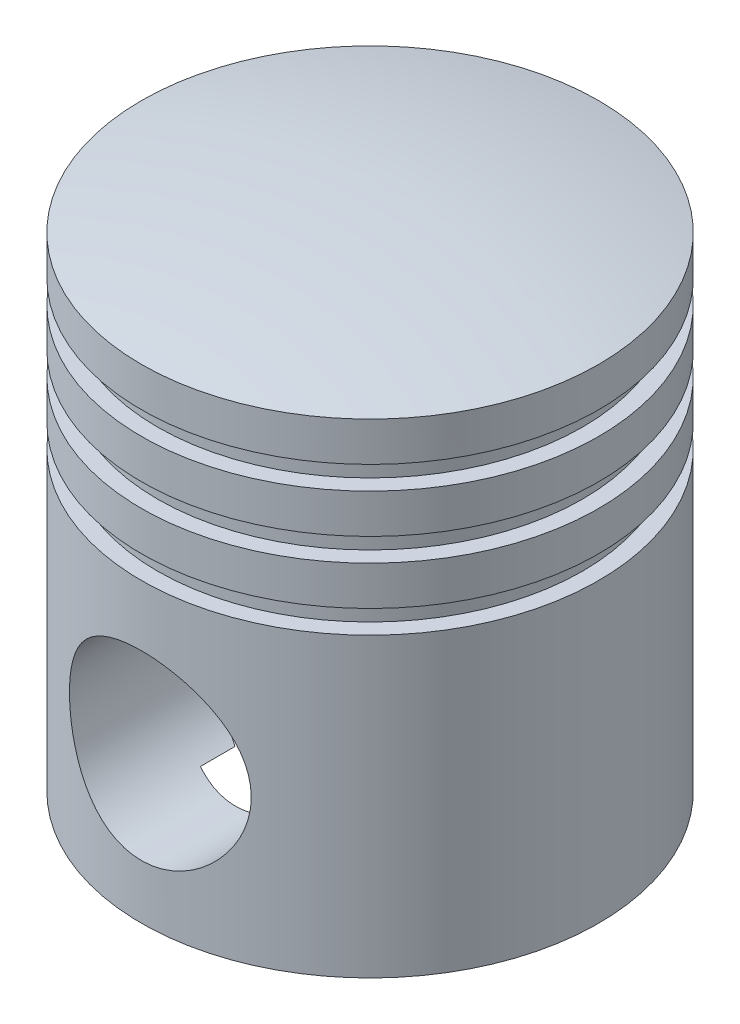
SolidWorks part; units mm, degrees
ref_plane "Front Plane" through (0, 0, 0) normal (0, 0, 1) x (1, 0, 0)
ref_plane "Top Plane" through (0, 0, 0) normal (0, 1, 0) x (1, 0, 0)
ref_plane "Right Plane" through (0, 0, 0) normal (1, 0, 0) x (0, 0, -1)
sketch "Sketch5" plane through (0, 0, 0) normal (0, 0, 1) x (1, 0, 0)
  line L0 (0, 0) -> (0, 123.193) construction
  line L1 (25, 0) -> (42.5, 0)
  line L2 (42.5, 0) -> (42.5, 55.2)
  line L3 (42.5, 55.2) -> (39.5, 55.2)
  line L4 (39.5, 55.2) -> (39.5, 59.5)
  line L5 (39.5, 59.5) -> (42.5, 59.5)
  line L6 (42.5, 59.5) -> (42.5, 66.8)
  line L7 (42.5, 66.8) -> (39.5, 66.8)
  line L8 (39.5, 66.8) -> (39.5, 71.1)
  line L9 (39.5, 71.1) -> (42.5, 71.1)
  line L10 (42.5, 71.1) -> (42.5, 78.4)
  line L11 (42.5, 78.4) -> (39.5, 78.4)
  line L12 (39.5, 78.4) -> (39.5, 82.7)
  line L13 (39.5, 82.7) -> (42.5, 82.7)
  line L14 (42.5, 82.7) -> (42.5, 90)
  line L16 (0, 90) -> (0, 85)
  line L17 (0, 85) -> (38, 85)
  line L18 (38, 85) -> (38, 49.5)
  line L19 (38, 49.5) -> (19, 49.5)
  line L21 (19, 49.5) -> (19, 12)
  line L22 (19, 12) -> (25, 12)
  line L23 (25, 12) -> (25, 0)
  line L24 (0, 90) -> (0, 95)
  arc A0 (42.5, 90) -> (0, 95) centre (0, -88.125) ccw
  point P25 (19, 30.75)
  dimension "D3" = 38
  dimension "D4" = 50
  dimension "D5" = 4.3
  dimension "D6" = 4.3
  dimension "D7" = 7.3
  dimension "D8" = 7.3
  dimension "D9" = 7.3
  dimension "D10" = 4.3
  dimension "D11" = 76
  dimension "D12" = 79
  dimension "D13" = 85
  dimension "D14" = 85
  dimension "D15" = 12
  dimension "D16" = 49.5
revolve "Revolve1" add sketch "Sketch5" angle 360 about L0
sketch "Sketch6" plane through (0, 0, 0) normal (0, 0, 1) x (1, 0, 0)
  line L0 (0, 0) -> (0, 77.2304) construction
  circle A0 centre (0, 27) radius 16.9
  dimension "D1" = 33.8
  dimension "D2" = 27
extrude "Cut-Extrude1" cut sketch "Sketch6" against normal through all both and the other way through all
